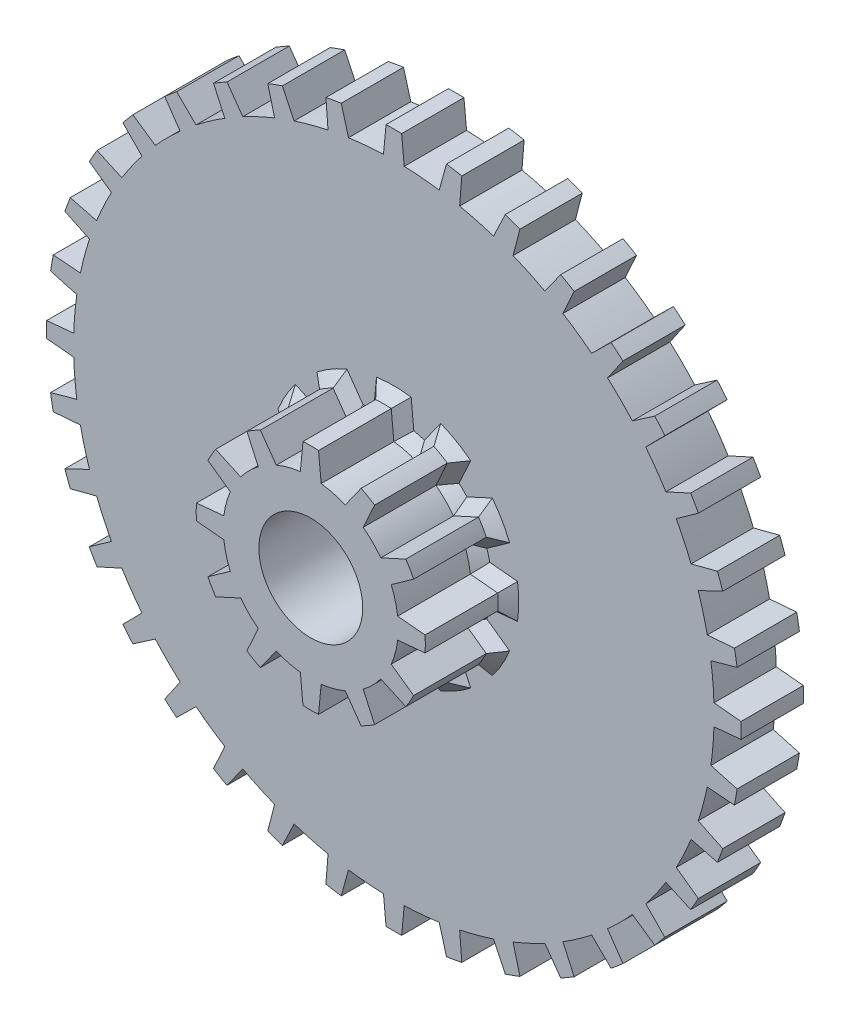
SolidWorks part; units mm, degrees
material "6061-T6 (SS)"
ref_plane "Alzado" through (0, 0, 0) normal (0, 0, 1) x (1, 0, 0)
ref_plane "Planta" through (0, 0, 0) normal (0, 1, 0) x (1, 0, 0)
ref_plane "Vista lateral" through (0, 0, 0) normal (1, 0, 0) x (0, 0, -1)
sketch "Croquis1" plane through (0, 0, 0) normal (0, 0, 1) x (1, 0, 0)
  line L0 (0, 0) -> (0, 14.5885) construction
  line L1 (-0.375, 16.7142) -> (-0.5, 15.4103)
  line L2 (0.375, 16.7142) -> (0.5, 15.4103)
  line L3 (3.2717, 16.3952) -> (3.1684, 15.0894)
  line L4 (2.5331, 16.5254) -> (2.1836, 15.263)
  line L5 (6.069, 15.578) -> (5.7405, 14.3099)
  line L6 (5.3642, 15.8345) -> (4.8008, 14.652)
  line L7 (8.6819, 14.2874) -> (8.1382, 13.0957)
  line L8 (8.0323, 14.6624) -> (7.2721, 13.5957)
  line L9 (11.031, 12.5628) -> (10.2886, 11.4836)
  line L10 (10.4564, 13.0449) -> (9.5225, 12.1264)
  line L11 (13.0449, 10.4564) -> (12.1264, 9.5225)
  line L12 (12.5628, 11.031) -> (11.4836, 10.2886)
  line L13 (14.6624, 8.0323) -> (13.5957, 7.2721)
  line L14 (14.2874, 8.6819) -> (13.0957, 8.1382)
  line L15 (15.8345, 5.3642) -> (14.652, 4.8008)
  line L16 (15.578, 6.069) -> (14.3099, 5.7405)
  line L17 (16.5254, 2.5331) -> (15.263, 2.1836)
  line L18 (16.3952, 3.2717) -> (15.0894, 3.1684)
  line L19 (16.7142, -0.375) -> (15.4103, -0.5)
  line L20 (16.7142, 0.375) -> (15.4103, 0.5)
  line L21 (16.3952, -3.2717) -> (15.0894, -3.1684)
  line L22 (16.5254, -2.5331) -> (15.263, -2.1836)
  line L23 (15.578, -6.069) -> (14.3099, -5.7405)
  line L24 (15.8345, -5.3642) -> (14.652, -4.8008)
  line L25 (14.2874, -8.6819) -> (13.0957, -8.1382)
  line L26 (14.6624, -8.0323) -> (13.5957, -7.2721)
  line L27 (12.5628, -11.031) -> (11.4836, -10.2886)
  line L28 (13.0449, -10.4564) -> (12.1264, -9.5225)
  line L29 (10.4564, -13.0449) -> (9.5225, -12.1264)
  line L30 (11.031, -12.5628) -> (10.2886, -11.4836)
  line L31 (8.0323, -14.6624) -> (7.2721, -13.5957)
  line L32 (8.6819, -14.2874) -> (8.1382, -13.0957)
  line L33 (5.3642, -15.8345) -> (4.8008, -14.652)
  line L34 (6.069, -15.578) -> (5.7405, -14.3099)
  line L35 (2.5331, -16.5254) -> (2.1836, -15.263)
  line L36 (3.2717, -16.3952) -> (3.1684, -15.0894)
  line L37 (-0.375, -16.7142) -> (-0.5, -15.4103)
  line L38 (0.375, -16.7142) -> (0.5, -15.4103)
  line L39 (-3.2717, -16.3952) -> (-3.1684, -15.0894)
  line L40 (-2.5331, -16.5254) -> (-2.1836, -15.263)
  line L41 (-6.069, -15.578) -> (-5.7405, -14.3099)
  line L42 (-5.3642, -15.8345) -> (-4.8008, -14.652)
  line L43 (-8.6819, -14.2874) -> (-8.1382, -13.0957)
  line L44 (-8.0323, -14.6624) -> (-7.2721, -13.5957)
  line L45 (-11.031, -12.5628) -> (-10.2886, -11.4836)
  line L46 (-10.4564, -13.0449) -> (-9.5225, -12.1264)
  line L47 (-13.0449, -10.4564) -> (-12.1264, -9.5225)
  line L48 (-12.5628, -11.031) -> (-11.4836, -10.2886)
  line L49 (-14.6624, -8.0323) -> (-13.5957, -7.2721)
  line L50 (-14.2874, -8.6819) -> (-13.0957, -8.1382)
  line L51 (-15.8345, -5.3642) -> (-14.652, -4.8008)
  line L52 (-15.578, -6.069) -> (-14.3099, -5.7405)
  line L53 (-16.5254, -2.5331) -> (-15.263, -2.1836)
  line L54 (-16.3952, -3.2717) -> (-15.0894, -3.1684)
  line L55 (-16.7142, 0.375) -> (-15.4103, 0.5)
  line L56 (-16.7142, -0.375) -> (-15.4103, -0.5)
  line L57 (-16.3952, 3.2717) -> (-15.0894, 3.1684)
  line L58 (-16.5254, 2.5331) -> (-15.263, 2.1836)
  line L59 (-15.578, 6.069) -> (-14.3099, 5.7405)
  line L60 (-15.8345, 5.3642) -> (-14.652, 4.8008)
  line L61 (-14.2874, 8.6819) -> (-13.0957, 8.1382)
  line L62 (-14.6624, 8.0323) -> (-13.5957, 7.2721)
  line L63 (-12.5628, 11.031) -> (-11.4836, 10.2886)
  line L64 (-13.0449, 10.4564) -> (-12.1264, 9.5225)
  line L65 (-10.4564, 13.0449) -> (-9.5225, 12.1264)
  line L66 (-11.031, 12.5628) -> (-10.2886, 11.4836)
  line L67 (-8.0323, 14.6624) -> (-7.2721, 13.5957)
  line L68 (-8.6819, 14.2874) -> (-8.1382, 13.0957)
  line L69 (-5.3642, 15.8345) -> (-4.8008, 14.652)
  line L70 (-6.069, 15.578) -> (-5.7405, 14.3099)
  line L71 (-2.5331, 16.5254) -> (-2.1836, 15.263)
  line L72 (-3.2717, 16.3952) -> (-3.1684, 15.0894)
  arc A0 (-10.4564, 13.0449) -> (-11.031, 12.5628) centre (0, 0) ccw
  arc A1 (2.1836, 15.263) -> (0.5, 15.4103) centre (0, 0) ccw
  arc A2 (-12.5628, 11.031) -> (-13.0449, 10.4564) centre (0, 0) ccw
  arc A3 (-14.2874, 8.6819) -> (-14.6624, 8.0323) centre (0, 0) ccw
  arc A4 (-15.578, 6.069) -> (-15.8345, 5.3642) centre (0, 0) ccw
  arc A5 (-16.3952, 3.2717) -> (-16.5254, 2.5331) centre (0, 0) ccw
  arc A6 (-16.7142, 0.375) -> (-16.7142, -0.375) centre (0, 0) ccw
  arc A7 (-16.5254, -2.5331) -> (-16.3952, -3.2717) centre (0, 0) ccw
  arc A8 (-15.8345, -5.3642) -> (-15.578, -6.069) centre (0, 0) ccw
  arc A9 (-14.6624, -8.0323) -> (-14.2874, -8.6819) centre (0, 0) ccw
  arc A10 (-13.0449, -10.4564) -> (-12.5628, -11.031) centre (0, 0) ccw
  arc A11 (3.2717, 16.3952) -> (2.5331, 16.5254) centre (0, 0) ccw
  arc A12 (0.375, 16.7142) -> (-0.375, 16.7142) centre (0, 0) ccw
  arc A13 (-5.3642, 15.8345) -> (-6.069, 15.578) centre (0, 0) ccw
  arc A14 (-8.0323, 14.6624) -> (-8.6819, 14.2874) centre (0, 0) ccw
  arc A15 (-2.5331, 16.5254) -> (-3.2717, 16.3952) centre (0, 0) ccw
  arc A16 (6.069, 15.578) -> (5.3642, 15.8345) centre (0, 0) ccw
  arc A17 (8.6819, 14.2874) -> (8.0323, 14.6624) centre (0, 0) ccw
  arc A18 (11.031, 12.5628) -> (10.4564, 13.0449) centre (0, 0) ccw
  arc A19 (13.0449, 10.4564) -> (12.5628, 11.031) centre (0, 0) ccw
  arc A20 (14.6624, 8.0323) -> (14.2874, 8.6819) centre (0, 0) ccw
  arc A21 (15.8345, 5.3642) -> (15.578, 6.069) centre (0, 0) ccw
  arc A22 (16.5254, 2.5331) -> (16.3952, 3.2717) centre (0, 0) ccw
  arc A23 (16.7142, -0.375) -> (16.7142, 0.375) centre (0, 0) ccw
  arc A24 (16.3952, -3.2717) -> (16.5254, -2.5331) centre (0, 0) ccw
  arc A25 (15.578, -6.069) -> (15.8345, -5.3642) centre (0, 0) ccw
  arc A26 (8.0323, -14.6624) -> (8.6819, -14.2874) centre (0, 0) ccw
  arc A27 (5.3642, -15.8345) -> (6.069, -15.578) centre (0, 0) ccw
  arc A28 (2.5331, -16.5254) -> (3.2717, -16.3952) centre (0, 0) ccw
  arc A29 (-3.2717, -16.3952) -> (-2.5331, -16.5254) centre (0, 0) ccw
  arc A30 (-6.069, -15.578) -> (-5.3642, -15.8345) centre (0, 0) ccw
  arc A31 (-8.6819, -14.2874) -> (-8.0323, -14.6624) centre (0, 0) ccw
  arc A32 (-11.031, -12.5628) -> (-10.4564, -13.0449) centre (0, 0) ccw
  arc A33 (10.4564, -13.0449) -> (11.031, -12.5628) centre (0, 0) ccw
  arc A34 (12.5628, -11.031) -> (13.0449, -10.4564) centre (0, 0) ccw
  arc A35 (14.2874, -8.6819) -> (14.6624, -8.0323) centre (0, 0) ccw
  arc A36 (4.8008, 14.652) -> (3.1684, 15.0894) centre (0, 0) ccw
  arc A37 (7.2721, 13.5957) -> (5.7405, 14.3099) centre (0, 0) ccw
  arc A38 (-3.1684, 15.0894) -> (-4.8008, 14.652) centre (0, 0) ccw
  arc A39 (-0.5, 15.4103) -> (-2.1836, 15.263) centre (0, 0) ccw
  arc A40 (-5.7405, 14.3099) -> (-7.2721, 13.5957) centre (0, 0) ccw
  arc A41 (-8.1382, 13.0957) -> (-9.5225, 12.1264) centre (0, 0) ccw
  arc A42 (-10.2886, 11.4836) -> (-11.4836, 10.2886) centre (0, 0) ccw
  arc A43 (9.5225, 12.1264) -> (8.1382, 13.0957) centre (0, 0) ccw
  arc A44 (11.4836, 10.2886) -> (10.2886, 11.4836) centre (0, 0) ccw
  arc A45 (13.0957, 8.1382) -> (12.1264, 9.5225) centre (0, 0) ccw
  arc A46 (14.3099, 5.7405) -> (13.5957, 7.2721) centre (0, 0) ccw
  arc A47 (15.0894, 3.1684) -> (14.652, 4.8008) centre (0, 0) ccw
  arc A48 (15.4103, 0.5) -> (15.263, 2.1836) centre (0, 0) ccw
  arc A49 (15.263, -2.1836) -> (15.4103, -0.5) centre (0, 0) ccw
  arc A50 (14.652, -4.8008) -> (15.0894, -3.1684) centre (0, 0) ccw
  arc A51 (13.5957, -7.2721) -> (14.3099, -5.7405) centre (0, 0) ccw
  arc A52 (12.1264, -9.5225) -> (13.0957, -8.1382) centre (0, 0) ccw
  arc A53 (10.2886, -11.4836) -> (11.4836, -10.2886) centre (0, 0) ccw
  arc A54 (8.1382, -13.0957) -> (9.5225, -12.1264) centre (0, 0) ccw
  arc A55 (5.7405, -14.3099) -> (7.2721, -13.5957) centre (0, 0) ccw
  arc A56 (3.1684, -15.0894) -> (4.8008, -14.652) centre (0, 0) ccw
  arc A57 (0.5, -15.4103) -> (2.1836, -15.263) centre (0, 0) ccw
  arc A58 (-2.1836, -15.263) -> (-0.5, -15.4103) centre (0, 0) ccw
  arc A59 (-4.8008, -14.652) -> (-3.1684, -15.0894) centre (0, 0) ccw
  arc A60 (-7.2721, -13.5957) -> (-5.7405, -14.3099) centre (0, 0) ccw
  arc A61 (-9.5225, -12.1264) -> (-8.1382, -13.0957) centre (0, 0) ccw
  arc A62 (-11.4836, -10.2886) -> (-10.2886, -11.4836) centre (0, 0) ccw
  arc A63 (-13.0957, -8.1382) -> (-12.1264, -9.5225) centre (0, 0) ccw
  arc A64 (-14.3099, -5.7405) -> (-13.5957, -7.2721) centre (0, 0) ccw
  arc A65 (-15.0894, -3.1684) -> (-14.652, -4.8008) centre (0, 0) ccw
  arc A66 (-15.4103, -0.5) -> (-15.263, -2.1836) centre (0, 0) ccw
  arc A67 (-15.263, 2.1836) -> (-15.4103, 0.5) centre (0, 0) ccw
  arc A68 (-14.652, 4.8008) -> (-15.0894, 3.1684) centre (0, 0) ccw
  arc A69 (-13.5957, 7.2721) -> (-14.3099, 5.7405) centre (0, 0) ccw
  arc A70 (-12.1264, 9.5225) -> (-13.0957, 8.1382) centre (0, 0) ccw
  arc A71 (-0.375, -16.7142) -> (0.375, -16.7142) centre (0, 0) ccw
  circle A72 centre (0, 0) radius 2.5
  arc A73 (-3.9906, 14.8931) -> (-1.3438, 15.3598) centre (0, 0) cw construction
  point P151 (0, 0)
  dimension "D1" = 1.3
  dimension "D6" = 5
  dimension "D5" = 1.69
  dimension "D2" = 1
  dimension "D3" = 0.75
  dimension "D4" = 36
extrude "Saliente-Extruir1" add sketch "Croquis1" along normal blind 3
sketch "Croquis2" plane through (0, 0, 3) normal (0, 0, 1) x (1, 0, 0)
  line L0 (0, 0) -> (0, 3.1536) construction
  line L1 (-0.375, 5.5012) -> (-0.5, 4.1842)
  line L2 (0.375, 5.5012) -> (0.5, 4.1842)
  line L3 (3.0754, 4.5767) -> (2.5251, 3.3737)
  line L4 (2.4259, 4.9517) -> (1.6591, 3.8737)
  line L5 (4.9517, 2.4259) -> (3.8737, 1.6591)
  line L6 (4.5767, 3.0754) -> (3.3737, 2.5251)
  line L7 (5.5012, -0.375) -> (4.1842, -0.5)
  line L8 (5.5012, 0.375) -> (4.1842, 0.5)
  line L9 (4.5767, -3.0754) -> (3.3737, -2.5251)
  line L10 (4.9517, -2.4259) -> (3.8737, -1.6591)
  line L11 (2.4259, -4.9517) -> (1.6591, -3.8737)
  line L12 (3.0754, -4.5767) -> (2.5251, -3.3737)
  line L13 (-0.375, -5.5012) -> (-0.5, -4.1842)
  line L14 (0.375, -5.5012) -> (0.5, -4.1842)
  line L15 (-3.0754, -4.5767) -> (-2.5251, -3.3737)
  line L16 (-2.4259, -4.9517) -> (-1.6591, -3.8737)
  line L17 (-4.9517, -2.4259) -> (-3.8737, -1.6591)
  line L18 (-4.5767, -3.0754) -> (-3.3737, -2.5251)
  line L19 (-5.5012, 0.375) -> (-4.1842, 0.5)
  line L20 (-5.5012, -0.375) -> (-4.1842, -0.5)
  line L21 (-4.5767, 3.0754) -> (-3.3737, 2.5251)
  line L22 (-4.9517, 2.4259) -> (-3.8737, 1.6591)
  line L23 (-2.4259, 4.9517) -> (-1.6591, 3.8737)
  line L24 (-3.0754, 4.5767) -> (-2.5251, 3.3737)
  circle A0 centre (0, 0) radius 2.5
  arc A1 (-0.5, 4.1842) -> (-1.6591, 3.8737) centre (0, 0) ccw
  arc A2 (-2.4259, 4.9517) -> (-3.0754, 4.5767) centre (0, 0) ccw
  arc A3 (-4.5767, 3.0754) -> (-4.9517, 2.4259) centre (0, 0) ccw
  arc A4 (-5.5012, 0.375) -> (-5.5012, -0.375) centre (0, 0) ccw
  arc A5 (-4.9517, -2.4259) -> (-4.5767, -3.0754) centre (0, 0) ccw
  arc A6 (-3.0754, -4.5767) -> (-2.4259, -4.9517) centre (0, 0) ccw
  arc A7 (-0.375, -5.5012) -> (0.375, -5.5012) centre (0, 0) ccw
  arc A8 (2.4259, -4.9517) -> (3.0754, -4.5767) centre (0, 0) ccw
  arc A9 (4.5767, -3.0754) -> (4.9517, -2.4259) centre (0, 0) ccw
  arc A10 (5.5012, -0.375) -> (5.5012, 0.375) centre (0, 0) ccw
  arc A11 (4.9517, 2.4259) -> (4.5767, 3.0754) centre (0, 0) ccw
  arc A12 (3.0754, 4.5767) -> (2.4259, 4.9517) centre (0, 0) ccw
  arc A13 (0.375, 5.5012) -> (-0.375, 5.5012) centre (0, 0) ccw
  arc A14 (1.6591, 3.8737) -> (0.5, 4.1842) centre (0, 0) ccw
  arc A15 (3.3737, 2.5251) -> (2.5251, 3.3737) centre (0, 0) ccw
  arc A16 (4.1842, 0.5) -> (3.8737, 1.6591) centre (0, 0) ccw
  arc A17 (3.8737, -1.6591) -> (4.1842, -0.5) centre (0, 0) ccw
  arc A18 (2.5251, -3.3737) -> (3.3737, -2.5251) centre (0, 0) ccw
  arc A19 (0.5, -4.1842) -> (1.6591, -3.8737) centre (0, 0) ccw
  arc A20 (-1.6591, -3.8737) -> (-0.5, -4.1842) centre (0, 0) ccw
  arc A21 (-3.3737, -2.5251) -> (-2.5251, -3.3737) centre (0, 0) ccw
  arc A22 (-4.1842, -0.5) -> (-3.8737, -1.6591) centre (0, 0) ccw
  arc A23 (-3.8737, 1.6591) -> (-4.1842, 0.5) centre (0, 0) ccw
  arc A24 (-2.5251, 3.3737) -> (-3.3737, 2.5251) centre (0, 0) ccw
  circle A25 centre (0, 0) radius 2.5 construction
  point P57 (0, 0)
  dimension "D1" = 1.3
  dimension "D2" = 1
  dimension "D3" = 0.75
  dimension "D5" = 1.2
  dimension "D4" = 12
extrude "Saliente-Extruir2" add sketch "Croquis2" along normal blind 4
chamfer "Chaflán3" distance 0.5 angle 45 48 edges at (-1.0907, 4.0704, 3) (-2.0425, 4.4127, 3) (-2.757, 4.7753, 3) (-2.8003, 3.9752, 3) (-2.9798, 2.9798, 3) (-3.9752, 2.8003, 3) (-4.7753, 2.757, 3) (-4.4127, 2.0425, 3) (-4.0704, 1.0907, 3) (-4.8427, 0.4375, 3) (-5.514, 0, 3) (-4.8427, -0.4375, 3) (-4.0704, -1.0907, 3) (-4.4127, -2.0425, 3) (-4.7753, -2.757, 3) (-3.9752, -2.8003, 3) (-2.9798, -2.9798, 3) (-2.8003, -3.9752, 3) (-2.757, -4.7753, 3) (-2.0425, -4.4127, 3) (-1.0907, -4.0704, 3) (-0.4375, -4.8427, 3) (0, -5.514, 3) (0.4375, -4.8427, 3) (1.0907, -4.0704, 3) (2.0425, -4.4127, 3) (2.757, -4.7753, 3) (2.8003, -3.9752, 3) (2.9798, -2.9798, 3) (3.9752, -2.8003, 3) (4.7753, -2.757, 3) (4.4127, -2.0425, 3) (4.0704, -1.0907, 3) (4.8427, -0.4375, 3) (5.514, 0, 3) (4.8427, 0.4375, 3) (4.0704, 1.0907, 3) (4.4127, 2.0425, 3) (4.7753, 2.757, 3) (3.9752, 2.8003, 3) (2.9798, 2.9798, 3) (2.8003, 3.9752, 3) (2.757, 4.7753, 3) (2.0425, 4.4127, 3) (1.0907, 4.0704, 3) (0.4375, 4.8427, 3) (0, 5.514, 3) (-0.4375, 4.8427, 3)
